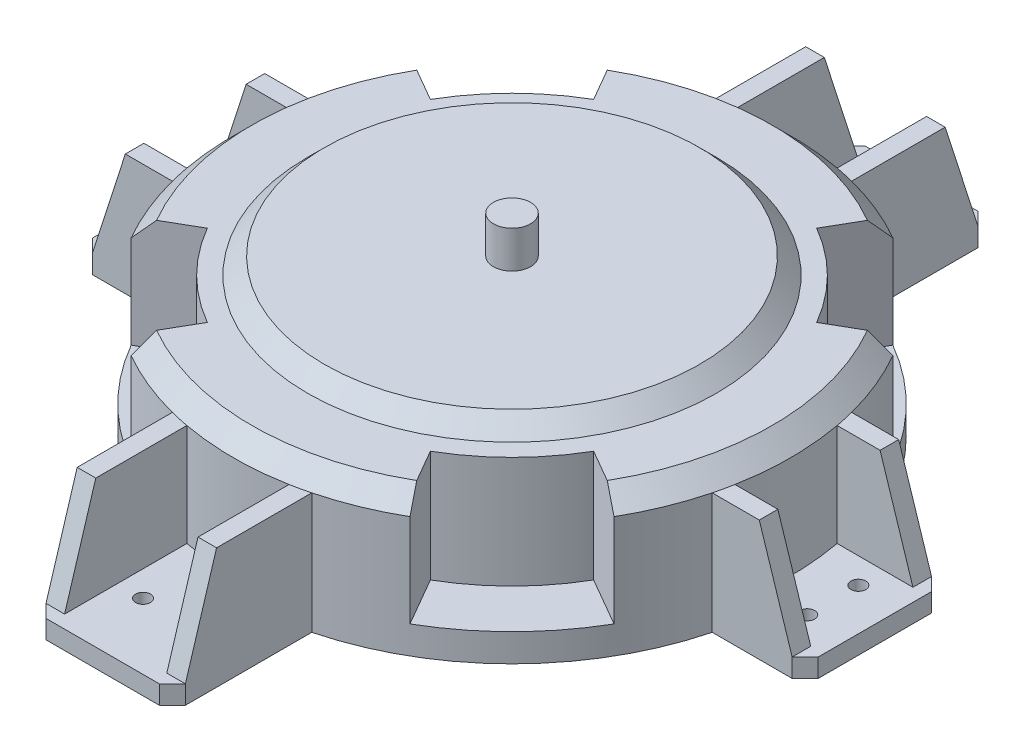
SolidWorks part; units mm, degrees
ref_plane "Front Plane" through (0, 0, 0) normal (0, 0, 1) x (1, 0, 0)
ref_plane "Top Plane" through (0, 0, 0) normal (0, 1, 0) x (1, 0, 0)
ref_plane "Right Plane" through (0, 0, 0) normal (1, 0, 0) x (0, 0, -1)
sketch "Sketch1" plane through (0, 0, 0) normal (0, 1, 0) x (1, 0, 0)
  circle A0 centre (0, 0) radius 150
  dimension "D1" = 300
extrude "Boss-Extrude1" add sketch "Sketch1" along normal blind 75
chamfer "Chamfer1" distance 10 angle 45 1 edges at (0, 75, 150)
sketch "Sketch2" plane through (0, 75, 0) normal (0, 1, 0) x (1, 0, 0)
  line L0 (0, 0) -> (-293.1043, 0) construction
  line L1 (-195.2369, 37.5) -> (-195.2369, -37.5) construction
  line L2 (-195.2369, 37.5) -> (-145.2369, 37.5)
  line L3 (-195.2369, 37.5) -> (-195.2369, -37.5)
  line L4 (-195.2369, -37.5) -> (-145.2369, -37.5)
  circle A0 centre (0, 0) radius 150 construction
  circle A1 centre (0, 0) radius 150
  point P6 (-195.2369, 0)
  dimension "D1" = 75
  dimension "D2" = 50
extrude "Boss-Extrude2" add sketch "Sketch2" along normal blind 10 from surface at -75 contours A1 L2 L3 L4 starting at face at (0, 0, 150)
chamfer "Chamfer2" distance 7 angle 45 2 edges at (-195.2369, 5, -37.5) (-195.2369, 5, 37.5)
sketch "Sketch6" plane through (0, 0, 37.5) normal (0, 0, 1) x (1, 0, 0)
  line L0 (-145.2369, 0) -> (-145.2369, 65)
  line L1 (-150, 65) -> (150, 65) construction
  line L2 (-145.2369, 65) -> (-170.5569, 65)
  line L3 (-170.5569, 65) -> (-188.2369, 10)
  line L4 (-188.2369, 10) -> (-188.2369, 0)
  line L5 (-188.2369, 0) -> (-145.2369, 0)
  dimension "D1" = 17.68
extrude "Boss-Extrude3" add sketch "Sketch6" against normal blind 10
sketch "Sketch7" plane through (0, 10, 0) normal (0, 1, 0) x (1, 0, 0)
  line L0 (-195.2369, 0) -> (-150, 0) construction
  line L1 (-195.2369, 30.5) -> (-195.2369, -30.5) construction
  line L2 (-172.6184, 0) -> (-172.6184, -27.5) construction
  line L3 (-188.2369, -27.5) -> (-147.4576, -27.5) construction
  arc A0 (-145.2369, -37.5) -> (-147.4576, -27.5) centre (0, 0) ccw construction
  circle A1 centre (-172.6184, -13.75) radius 4
  dimension "D1" = 8
extrude "Cut-Extrude1" cut sketch "Sketch7" against normal through all
sketch "Sketch8" plane through (0, 10, 0) normal (0, 1, 0) x (1, 0, 0)
  line L0 (-195.2369, 0) -> (-150, 0) construction
  line L1 (-195.2369, 30.5) -> (-195.2369, -30.5) construction
  arc A0 (-145.2369, -37.5) -> (-147.4576, -27.5) centre (0, 0) ccw construction
ref_plane "Plane1" through (0, 0, 0) normal (0, 0, 1) x (1, 0, 0)
mirror "Mirror2" about plane through (0, 0, 0) normal (0, 0, 1) of "Boss-Extrude3", "Cut-Extrude1"
sketch3d "3DSketch1"
  arc A0 (-145.2369, 0, 37.5) -> (-145.2369, 0, -37.5) centre (0, 0, 0) ccw construction
  arc A1 (-145.2369, 0, 37.5) -> (-145.2369, 0, -37.5) centre (0, 0, 0) ccw
  circle A2 centre (0, 0, 0) radius 150
  point P3 (0, 150, 0)
  point P4 (0, 150, 0)
  point P7 (0, 150, 0)
sketch "Sketch10" plane through (0, 0, 0) normal (0, -1, 0) x (1, 0, 0)
  line L0 (-145.2369, 37.5) -> (-188.2369, 37.5)
  line L1 (-188.2369, 37.5) -> (-195.2369, 30.5)
  line L2 (-195.2369, 30.5) -> (-195.2369, -30.5)
  line L3 (-195.2369, -30.5) -> (-188.2369, -37.5)
  line L4 (-188.2369, -37.5) -> (-145.2369, -37.5)
  arc A0 (-145.2369, 37.5) -> (-145.2369, -37.5) centre (0, 0) ccw
extrude "Boss-Extrude4" add sketch "Sketch10" along normal blind 0.1
sketch "Sketch11" plane through (0, 75, 0) normal (0, 1, 0) x (1, 0, 0)
  line L0 (0, 221.4176) -> (0, -245.7939) construction
  line L1 (-140, 0) -> (278.022, 0) construction
  line L2 (-37.5, 220.2369) -> (37.5, 220.2369) construction
  line L3 (37.5, 220.2369) -> (37.5, 145.2369)
  line L4 (37.5, 220.2369) -> (-37.5, 220.2369)
  line L5 (-37.5, 220.2369) -> (-37.5, 145.2369)
  line L6 (37.5, -220.2369) -> (37.5, -145.2369)
  line L7 (37.5, -220.2369) -> (-37.5, -220.2369)
  line L8 (-37.5, -220.2369) -> (-37.5, -145.2369)
  circle A0 centre (0, 0) radius 140 construction
  arc A1 (-145.2369, -37.5) -> (-145.2369, 37.5) centre (0, 0) ccw construction
  arc A2 (37.5, -145.2369) -> (-37.5, -145.2369) centre (0, 0) cw
  arc A3 (37.5, 145.2369) -> (-37.5, 145.2369) centre (0, 0) ccw
  point P11 (0, 220.2369)
  dimension "D1" = 75
  dimension "D2" = 75
extrude "Boss-Extrude8" add sketch "Sketch11" along normal blind 10 from offset 75 offset against normal yes
chamfer "Chamfer3" distance 7 angle 45 2 edges at (37.5, 5, -220.2369) (-37.5, 5, -220.2369)
sketch "Sketch14" plane through (-37.5, 0, 0) normal (-1, 0, 0) x (0, 0, 1)
  line L0 (-145.2369, 0) -> (-145.2369, 65)
  line L1 (-150, 65) -> (150, 65) construction
  line L2 (-145.2369, 65) -> (-195.5569, 65)
  line L3 (-195.5569, 65) -> (-213.2369, 10)
  line L4 (-213.2369, 10) -> (-213.2369, 0)
  line L5 (-213.2369, 0) -> (-145.2369, 0)
  dimension "D1" = 17.68
extrude "Boss-Extrude9" add sketch "Sketch14" against normal blind 10
ref_plane "Plane2" through (0, 0, 0) normal (-1, 0, 0) x (0, 0, 1)
mirror "Mirror3" about plane through (0, 0, 0) normal (-1, 0, 0) of "Boss-Extrude9"
sketch "Sketch16" plane through (0, 10, 0) normal (0, 1, 0) x (1, 0, 0)
  line L0 (0, 220.2369) -> (0, 150) construction
  line L1 (30.5, 220.2369) -> (-30.5, 220.2369) construction
  line L2 (0, 35.75) -> (0, -35.75) construction
  line L3 (0, 185.1184) -> (-27.5, 185.1184) construction
  line L4 (-27.5, 213.2369) -> (-27.5, 147.4576) construction
  arc A0 (-145.2369, -37.5) -> (-145.2369, 37.5) centre (0, 0) ccw construction
  circle A1 centre (-13.75, 185.1184) radius 4
  circle A2 centre (13.75, 185.1184) radius 4
  dimension "D1" = 8
extrude "Cut-Extrude2" cut sketch "Sketch16" against normal through all
chamfer "Chamfer4" distance 7 angle 45 2 edges at (-37.5, 5, 220.2369) (37.5, 5, 220.2369)
sketch "Sketch18" plane through (37.5, 0, 0) normal (1, 0, 0) x (0, 0, -1)
  line L0 (-145.2369, 0) -> (-145.2369, 65)
  line L1 (145.2369, 65) -> (-150, 65) construction
  line L2 (-145.2369, 65) -> (-196.4569, 65)
  line L3 (-196.4569, 65) -> (-213.2369, 10)
  line L4 (-213.2369, 10) -> (-213.2369, 0)
  line L5 (-213.2369, 0) -> (-145.2369, 0)
  dimension "D1" = 16.78
extrude "Boss-Extrude10" add sketch "Sketch18" against normal blind 10
ref_plane "Plane3" through (0, 0, 0) normal (1, 0, 0) x (0, 0, -1)
sketch "Sketch19" plane through (0, 10, 0) normal (0, 1, 0) x (1, 0, 0)
  line L0 (0, -149.3057) -> (0, -220.2369) construction
  line L1 (0, -35.75) -> (0, 35.75) construction
  line L2 (-30.5, -220.2369) -> (30.5, -220.2369) construction
  line L3 (0, -184.7713) -> (27.5, -184.7713) construction
  line L4 (27.5, -147.4576) -> (27.5, -213.2369) construction
  circle A0 centre (13.75, -184.7713) radius 4
  circle A1 centre (-13.75, -184.7713) radius 4
  dimension "D1" = 8
extrude "Cut-Extrude3" cut sketch "Sketch19" against normal through all
mirror "Mirror4" about plane through (0, 0, 0) normal (1, 0, 0) of "Boss-Extrude10"
sketch "Sketch20" plane through (0, 75, 0) normal (0, 1, 0) x (1, 0, 0)
  line L0 (150, 0) -> (294.0453, 0) construction
  line L1 (195.2369, 37.5) -> (195.2369, -37.5) construction
  line L2 (195.2369, 37.5) -> (145.2369, 37.5)
  line L3 (195.2369, 37.5) -> (195.2369, -37.5)
  line L4 (195.2369, -37.5) -> (145.2369, -37.5)
  arc A0 (-145.2369, -37.5) -> (-145.2369, 37.5) centre (0, 0) ccw construction
  arc A1 (145.2369, -37.5) -> (145.2369, 37.5) centre (0, 0) ccw
  point P6 (195.2369, 0)
  dimension "D1" = 75
  dimension "D2" = 50
extrude "Boss-Extrude11" add sketch "Sketch20" along normal blind 10 from offset 75 offset against normal yes
chamfer "Chamfer5" distance 7 angle 45 2 edges at (195.2369, 5, -37.5) (195.2369, 5, 37.5)
sketch "Sketch21" plane through (0, 0, -37.5) normal (0, 0, -1) x (-1, 0, 0)
  line L0 (-145.2369, 0) -> (-145.2369, 65)
  line L1 (-37.5, 65) -> (-150, 65) construction
  line L2 (-145.2369, 65) -> (-170.5569, 65)
  line L3 (-170.5569, 65) -> (-188.2369, 10)
  line L4 (-188.2369, 10) -> (-188.2369, 0)
  line L5 (-188.2369, 0) -> (-145.2369, 0)
  dimension "D1" = 17.68
extrude "Boss-Extrude12" add sketch "Sketch21" against normal blind 10
sketch "Sketch22" plane through (0, 10, 0) normal (0, 1, 0) x (1, 0, 0)
  line L0 (150, 0) -> (195.2369, 0) construction
  line L1 (195.2369, -30.5) -> (195.2369, 30.5) construction
  line L2 (172.6184, 0) -> (172.6184, 27.5) construction
  line L3 (188.2369, 27.5) -> (147.4576, 27.5) construction
  arc A0 (-145.2369, -37.5) -> (-145.2369, 37.5) centre (0, 0) ccw construction
  circle A1 centre (172.6184, 13.75) radius 4
  dimension "D1" = 8
extrude "Cut-Extrude4" cut sketch "Sketch22" against normal through all
ref_plane "Plane4" through (0, 0, 0) normal (0, 0, -1) x (-1, 0, 0)
mirror "Mirror5" about plane through (0, 0, 0) normal (0, 0, -1) of "Boss-Extrude12", "Cut-Extrude4"
sketch "Sketch23" plane through (0, 75, 0) normal (0, 1, 0) x (1, 0, 0)
  line L0 (-150, 0) -> (-120, 0) construction
  line L4 (-103.923, -60) -> (-129.9038, -75)
  line L5 (-60, -103.923) -> (-75, -129.9038)
  arc A2 (-103.923, -60) -> (-60, -103.923) centre (0, 0) ccw
  arc A3 (-129.9038, -75) -> (-75, -129.9038) centre (0, 0) ccw
extrude "Cut-Extrude5" cut sketch "Sketch23" against normal blind 60
pattern_circular "CirPattern31" count 4 over 360 about axis through (0, 75, 0) along (0, 1, 0) of "Cut-Extrude5"
sketch "Sketch24" plane through (0, 75, 0) normal (0, 1, 0) x (1, 0, 0)
  circle A0 centre (0, 0) radius 110
  dimension "D1" = 220
extrude "Boss-Extrude13" add sketch "Sketch24" along normal blind 9 draft 45
sketch "Sketch25" plane through (0, 84, 0) normal (0, 1, 0) x (1, 0, 0)
  circle A0 centre (0, 0) radius 10
  dimension "D1" = 20
extrude "Boss-Extrude14" add sketch "Sketch25" along normal blind 20
sketch "Sketch28" plane through (0, 10, 0) normal (0, 1, 0) x (1, 0, 0)
  circle A0 centre (-172.6184, 13.75) radius 4
  circle A1 centre (-172.6184, -13.75) radius 4
extrude "Cut-Extrude6" cut sketch "Sketch28" against normal through all
